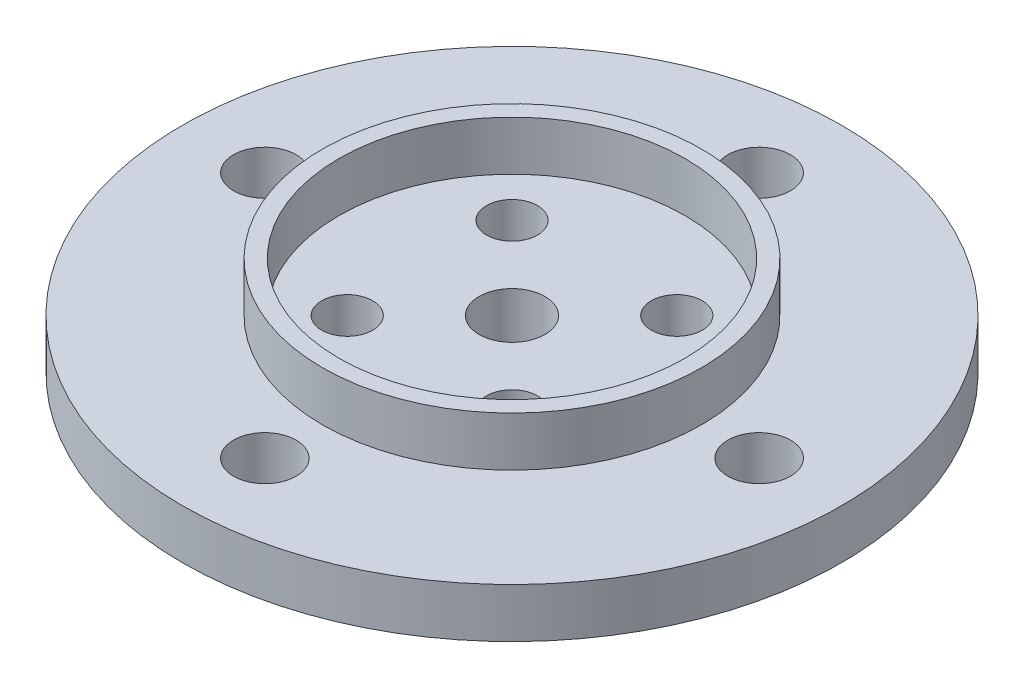
SolidWorks part; units mm, degrees
ref_plane "前视基准面" through (0, 0, 0) normal (0, 0, 1) x (1, 0, 0)
ref_plane "上视基准面" through (0, 0, 0) normal (0, 1, 0) x (1, 0, 0)
ref_plane "右视基准面" through (0, 0, 0) normal (1, 0, 0) x (0, 0, -1)
other "Configuration Table"
sketch "草图1" plane through (0, 0, 0) normal (0, 1, 0) x (1, 0, 0)
  line L1 (-5, -5) -> (5, -5)
  line L2 (-5, -5) -> (-5, 5)
  line L3 (-5, 5) -> (5, 5)
  line L4 (5, -5) -> (5, 5)
  line L5 (-5, -5) -> (5, 5) construction
  line L6 (-5, 5) -> (5, -5) construction
  circle A0 centre (0, 0) radius 20
  circle A1 centre (0, 0) radius 10
  circle A2 centre (0, 0) radius 15
  circle A3 centre (0, 15) radius 1.6
  circle A4 centre (15, 0) radius 1.6
  circle A5 centre (0, -15) radius 1.6
  circle A6 centre (-15, 0) radius 1.6
  circle A7 centre (-5, 5) radius 1.55
  circle A8 centre (5, 5) radius 1.55
  circle A9 centre (5, -5) radius 1.55
  circle A10 centre (-5, -5) radius 1.55
  circle A11 centre (0, 0) radius 2
  point P16 (0, 0)
  point P28 (0, 0)
  dimension "D1" = 40
  dimension "D2" = 30
  dimension "D3" = 3.2
  dimension "D7" = 3.1
  dimension "D9" = 4
  dimension "D5" = 10
  dimension "D6" = 10
  dimension "D4" = 4
  dimension "D8" = 4
extrude "凸台-拉伸1" add sketch "草图1" along normal blind 3 contours A0 A6 A2 A3 A4 A5 | A6 A2 A5 A4 A3 A1 | A1 A10 L2 A7 L3 A8 L4 A9 L1 | A10 L1 A9 L4 A8 L3 A7 L2 A11
sketch "草图2" plane through (0, 3, 0) normal (0, 1, 0) x (1, 0, 0)
  circle A0 centre (0, 0) radius 10.5
  circle A1 centre (0, 0) radius 11.5
  dimension "D1" = 21
  dimension "D2" = 23
extrude "凸台-拉伸2" add sketch "草图2" along normal blind 3
sketch "草图3" plane through (0, 0, 0) normal (0, -1, 0) x (1, 0, 0)
  circle A0 centre (0, 15) radius 1.9
  circle A1 centre (15, 0) radius 1.9
  circle A2 centre (0, -15) radius 1.9
  circle A3 centre (-15, 0) radius 1.9
  point P12 (0, 0)
  dimension "D1" = 3.8
  dimension "D2" = 4
extrude "切除-拉伸1" cut sketch "草图3" against normal blind 3
